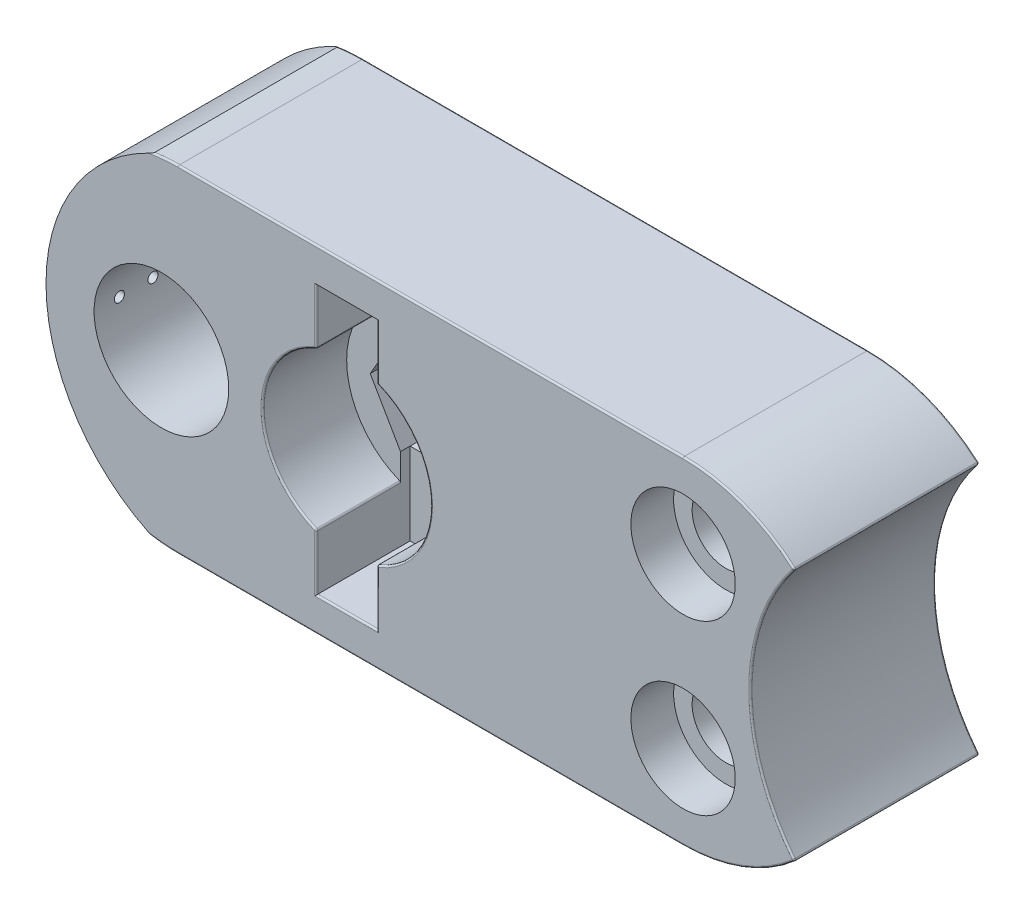
SolidWorks part; units mm, degrees
ref_plane "前视基准面" through (0, 0, 0) normal (0, 0, 1) x (1, 0, 0)
ref_plane "上视基准面" through (0, 0, 0) normal (0, 1, 0) x (1, 0, 0)
ref_plane "右视基准面" through (0, 0, 0) normal (1, 0, 0) x (0, 0, -1)
sketch "草图1" plane through (0, 0, 0) normal (0, 0, 1) x (1, 0, 0)
  line L0 (-100.0924, 0) -> (199.9076, 0) construction
  line L1 (-100.0924, 100) -> (199.9076, 100)
  line L2 (-100.0924, -100) -> (199.9076, -100)
  arc A0 (-100.0924, 100) -> (-100.0924, -100) centre (-100.0924, 0) ccw
  arc A1 (199.9076, -100) -> (199.9076, 100) centre (199.9076, 0) ccw
  circle A2 centre (-110.0924, 0) radius 40
  point P3 (49.9076, 0)
  point P10 (-200.0924, 0)
  dimension "D3" = 90
  dimension "D1" = 300
  dimension "D2" = 200
extrude "凸台-拉伸1" add sketch "草图1" along normal blind 110
ref_plane "基准面4" through (-100, 0, 0) normal (1, 0, 0) x (0, 0, -1)
sketch "草图2" plane through (-100, 0, 0) normal (1, 0, 0) x (0, 0, -1)
  line L0 (-110, 100) -> (-110, -100) construction
  circle A0 centre (-95, 0) radius 3
  circle A1 centre (-75, 0) radius 3
  circle A2 centre (-55, 0) radius 3
  dimension "D1" = 6
  dimension "D2" = 15
  dimension "D3" = 3
extrude "切除-拉伸2" cut sketch "草图2" against normal blind 150
sketch "草图3" plane through (0, 0, 110) normal (0, 0, 1) x (1, 0, 0)
  circle A0 centre (0, 0) radius 50
  dimension "D1" = 0
extrude "切除-拉伸3" cut sketch "草图3" against normal blind 50
sketch "草图4" plane through (0, 0, 60) normal (0, 0, 1) x (1, 0, 0)
  line L1 (36, 0) -> (18, 31.1769)
  line L2 (18, 31.1769) -> (-18, 31.1769)
  line L3 (-18, 31.1769) -> (-36, 0)
  line L4 (-36, 0) -> (-18, -31.1769)
  line L5 (-18, -31.1769) -> (18, -31.1769)
  line L6 (18, -31.1769) -> (36, 0)
  circle A0 centre (0, 0) radius 36 construction
extrude "切除-拉伸4" cut sketch "草图4" against normal blind 10
sketch "草图5" plane through (0, 0, 50) normal (0, 0, 1) x (1, 0, 0)
  line L1 (18, 80) -> (-18, 80)
  line L2 (18, 80) -> (18, -80)
  line L3 (18, -80) -> (-18, -80)
  line L4 (-18, 80) -> (-18, -80)
  line L5 (18, 80) -> (-18, -80) construction
  line L6 (18, -80) -> (-18, 80) construction
  point P0 (0, 0)
  dimension "D1" = 36
  dimension "D2" = 160
extrude "切除-拉伸7" cut sketch "草图5" along normal blind 122
sketch "草图6" plane through (0, 0, 50) normal (0, 0, 1) x (1, 0, 0)
  line L1 (36, 0) -> (18, 31.1769)
  line L2 (18, 31.1769) -> (-18, 31.1769)
  line L3 (-18, 31.1769) -> (-36, 0)
  line L4 (-36, 0) -> (-18, -31.1769)
  line L5 (-18, -31.1769) -> (18, -31.1769)
  line L6 (18, -31.1769) -> (36, 0)
  circle A0 centre (0, 0) radius 36 construction
extrude "切除-拉伸8" cut sketch "草图6" against normal blind 10
sketch "草图7" plane through (0, 0, 50) normal (0, 0, 1) x (1, 0, 0)
  line L0 (-18, 80) -> (18, 80) construction
  circle A0 centre (0, 62) radius 3
  point P4 (0, 80)
  dimension "D1" = 6
  dimension "D2" = 18
extrude "切除-拉伸9" cut sketch "草图7" against normal blind 10
mirror "镜向1" about plane through (0, 0, 0) normal (0, 1, 0) of "切除-拉伸9"
sketch "草图8" plane through (0, 0, 110) normal (0, 0, 1) x (1, 0, 0)
  line L0 (199.9076, 100) -> (199.9076, -100)
  line L1 (199.9076, -100) -> (199.9076, 0)
  line L2 (199.9076, 0) -> (199.9076, 100)
  circle A0 centre (199.9076, 50) radius 12.5
  dimension "D1" = 25
extrude "切除-拉伸12" cut sketch "草图8" against normal blind 200 contours L2 A0 | L2 A0
sketch "草图9" plane through (0, 0, 110) normal (0, 0, 1) x (1, 0, 0)
  circle A0 centre (199.9076, 50) radius 31
  circle M2 centre (199.9076, 50) radius 12.5
extrude "切除-拉伸13" cut sketch "草图9" against normal blind 25.4 contours A0 M2
ref_plane "基准面5" through (0, 0, 55) normal (0, 0, 1) x (1, 0, 0)
mirror "镜向3" about plane through (0, 0, 0) normal (0, 1, 0) of "切除-拉伸13", "切除-拉伸12" second plane through (0, 0, 55) second plane normal (0, 0, 1)
sketch "草图10" plane through (0, 0, 40) normal (0, 0, 1) x (1, 0, 0)
  line L1 (36, 0) -> (18, 31.1769)
  line L2 (18, 31.1769) -> (-18, 31.1769)
  line L3 (-18, 31.1769) -> (-36, 0)
  line L4 (-36, 0) -> (-18, -31.1769)
  line L5 (-18, -31.1769) -> (18, -31.1769)
  line L6 (18, -31.1769) -> (36, 0)
  line L7 (-18, 83.4512) -> (18, 83.4512)
  line L8 (-18, 83.4512) -> (-18, -83.4512)
  line L9 (-18, -83.4512) -> (18, -83.4512)
  line L10 (18, 83.4512) -> (18, -83.4512)
  line L11 (-18, 83.4512) -> (18, -83.4512) construction
  line L12 (-18, -83.4512) -> (18, 83.4512) construction
  circle A0 centre (0, 0) radius 36 construction
  circle A1 centre (0, 0) radius 36
  circle A2 centre (0, 0) radius 50
  line M7 (18, -31.1769) -> (36, 0)
  line M8 (36, 0) -> (18, 31.1769)
  line M10 (-18, 31.1769) -> (-36, 0)
  line M11 (-36, 0) -> (-18, -31.1769)
extrude "凸台-拉伸2" add sketch "草图10" along normal blind 4.3 contours L10 A2 A1 | L8 A2 A1 | A1 M8 | A1 M7 | A1 M11 | A1 M10
sketch "草图11" plane through (0, 0, 50) normal (0, 0, 1) x (1, 0, 0)
  line L0 (-18, 31.1769) -> (18, 31.1769)
  line L1 (-18, 80) -> (18, 80)
  line L2 (-18, 80) -> (-18, -80)
  line L3 (-18, -80) -> (18, -80)
  line L4 (18, 80) -> (18, -80)
  line L5 (-18, 80) -> (18, -80) construction
  line L6 (-18, -80) -> (18, 80) construction
  circle A0 centre (0, 62) radius 3
  point P0 (0, 0)
  circle M1 centre (0, 62) radius 3
  line M2 (-18, 31.1769) -> (18, 31.1769)
  line M3 (18, 31.1769) -> (18, 80)
  line M4 (18, 80) -> (-18, 80)
  line M5 (-18, 80) -> (-18, 31.1769)
extrude "凸台-拉伸3" add sketch "草图11" along normal blind 4.3 contours M5 M2 M3 M4 M1
mirror "镜向4" about plane through (0, 0, 0) normal (0, 1, 0) of "凸台-拉伸3"
sketch "草图12" plane through (0, 0, 110) normal (0, 0, 1) x (1, 0, 0)
  line L0 (199.9076, 100) -> (199.9076, -100)
  line L1 (199.9076, 0) -> (359.9076, 0)
  circle A0 centre (359.9076, 0) radius 120
  arc M6 (199.9076, -100) -> (199.9076, 100) centre (199.9076, 0) ccw
  dimension "D1" = 160
extrude "切除-拉伸14" cut sketch "草图12" against normal blind 200 contours L1 A0 M6 | A0 L1 M6
sketch "草图13" plane through (0, 0, 84.6) normal (0, 0, 1) x (1, 0, 0)
  circle A0 centre (199.9076, 50) radius 20
extrude "切除-拉伸15" cut sketch "草图13" against normal blind 200
mirror "镜向5" about plane through (0, 0, 0) normal (0, 1, 0) of "切除-拉伸15"
sketch "草图14" plane through (0, 0, 110) normal (0, 0, 1) x (1, 0, 0)
  circle A0 centre (-70.0924, 0) radius 108.5853
  circle A1 centre (-110.0924, 0) radius 40 construction
  point P4 (0, 0)
  arc M5 (-100.0924, 100) -> (-100.0924, -100) centre (-100.0924, 0) ccw
extrude "切除-拉伸16" cut sketch "草图14" against normal blind 200 contours A0 M5
fillet "圆角1" radius 1 16 edges at (-107.5362, -99.7226, 0) (49.9076, -100, 0) (-107.5362, 99.7226, 0) (49.9076, 100, 0) (-107.5362, -99.7226, 110) (49.9076, -100, 110) (-107.5362, 99.7226, 110) (49.9076, 100, 110) (235.3292, -93.5164, 0) (239.9076, 0, 0) (235.3292, 93.5164, 0) (266.1576, 74.9062, 55) (266.1576, -74.9062, 55) (235.3292, -93.5164, 110) (239.9076, 0, 110) (235.3292, 93.5164, 110)
fillet "圆角2" radius 1 11 edges at (18, -46.6476, 85) (18, 46.6476, 85) (18, 63.3238, 110) (-18, 63.3238, 110) (-18, -46.6476, 85) (-18, 46.6476, 85) (-50, 0, 110) (-18, -63.3238, 110) (0, -80, 110) (18, -63.3238, 110) (50, 0, 110)
